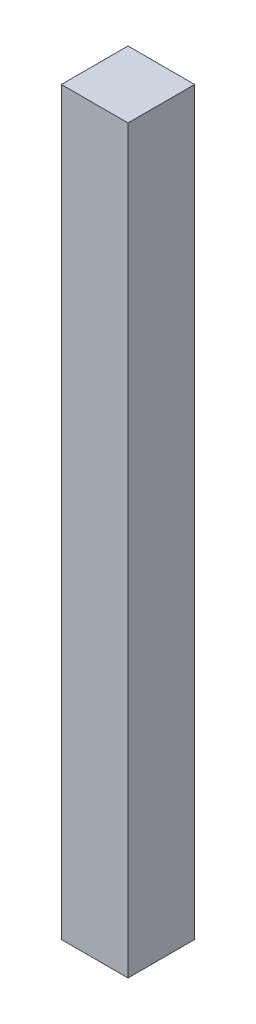
SolidWorks part; units mm, degrees
ref_plane "Front Plane" through (0, 0, 0) normal (0, 0, 1) x (1, 0, 0)
ref_plane "Top Plane" through (0, 0, 0) normal (0, 1, 0) x (1, 0, 0)
ref_plane "Right Plane" through (0, 0, 0) normal (1, 0, 0) x (0, 0, -1)
other "Configuration Table"
sketch "Sketch1" plane through (0, 0, 0) normal (0, 0, 1) x (1, 0, 0)
  line L1 (637, 1180) -> (655, 1180)
  line L2 (637, 1180) -> (637, 1380)
  line L3 (637, 1380) -> (655, 1380)
  line L4 (655, 1180) -> (655, 1380)
extrude "TOPPING_klape_kat2_gazli_amortisor_2_1" add sketch "Sketch1" along normal blind 18 from offset 8 separate body
